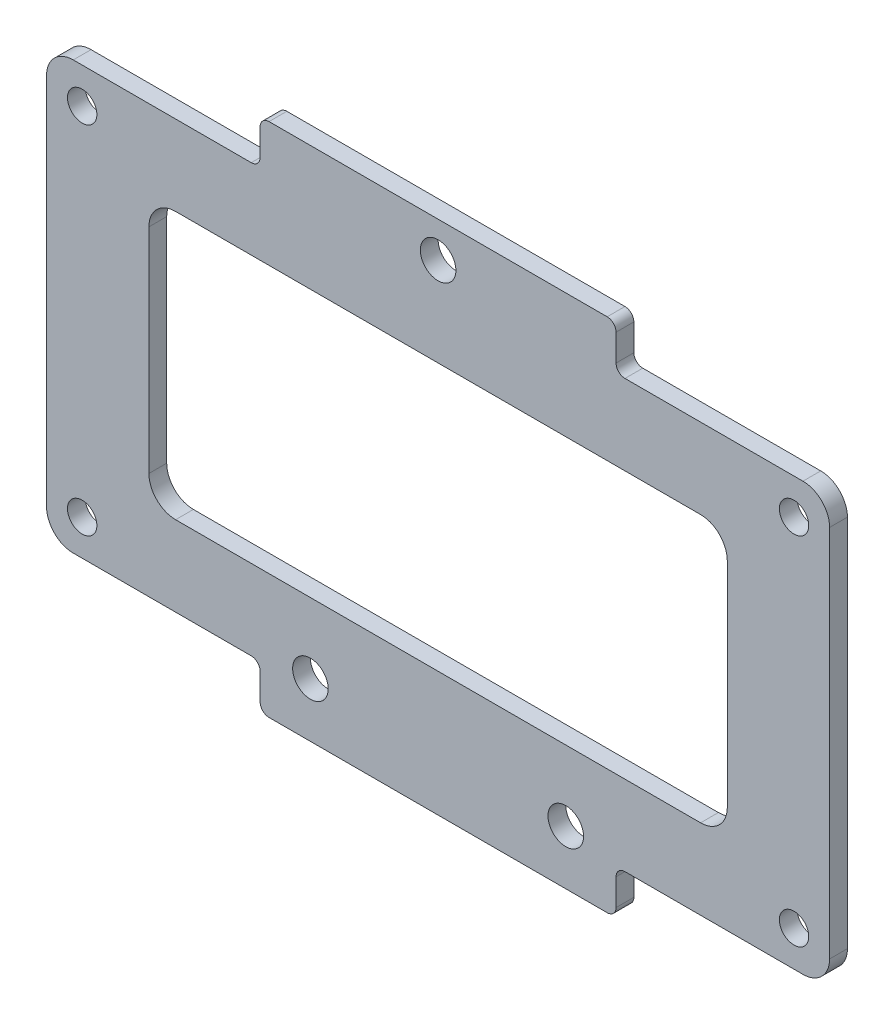
SolidWorks part; units mm, degrees
material "A-玻璃纤维"
ref_plane "前视基准面" through (0, 0, 0) normal (0, 0, 1) x (1, 0, 0)
ref_plane "上视基准面" through (0, 0, 0) normal (0, 1, 0) x (1, 0, 0)
ref_plane "右视基准面" through (0, 0, 0) normal (1, 0, 0) x (0, 0, -1)
sketch "草图1" plane through (0, 0, 0) normal (0, 0, 1) x (1, 0, 0)
  line L1 (40, -20) -> (-40, -20) construction
  line L2 (40, -20) -> (40, 20) construction
  line L3 (40, 20) -> (-40, 20) construction
  line L4 (-40, -20) -> (-40, 20) construction
  line L5 (40, -20) -> (-40, 20) construction
  line L6 (40, 20) -> (-40, -20) construction
  line L7 (44, -24) -> (-44, -24)
  line L8 (44, -24) -> (44, 24)
  line L9 (44, 24) -> (-44, 24)
  line L10 (-44, -24) -> (-44, 24)
  line L11 (44, -24) -> (-44, 24) construction
  line L12 (44, 24) -> (-44, -24) construction
  circle A0 centre (-40, 20) radius 1.65
  circle A1 centre (40, 20) radius 1.65
  circle A2 centre (40, -20) radius 1.65
  circle A3 centre (-40, -20) radius 1.65
  point P0 (0, 0)
  point P10 (0, 0)
  dimension "D3" = 3.3
  dimension "D4" = 3.3
  dimension "D5" = 3.3
  dimension "D6" = 3.3
  dimension "D1" = 40
  dimension "D2" = 80
  dimension "D7" = 48
  dimension "D8" = 88
extrude "凸台-拉伸1" add sketch "草图1" along normal blind 2
fillet "圆角1" radius 3 4 edges at (44, -24, 1) (44, 24, 1) (-44, -24, 1) (-44, 24, 1)
sketch "草图3" plane through (0, 0, 2) normal (0, 0, 1) x (1, 0, 0)
  line L0 (41, 24) -> (-41, 24) construction
  line L1 (20, 19) -> (-20, 19)
  line L2 (20, 19) -> (20, 29)
  line L3 (20, 29) -> (-20, 29)
  line L4 (-20, 19) -> (-20, 29)
  line L5 (20, 19) -> (-20, 29) construction
  line L6 (20, 29) -> (-20, 19) construction
  line L7 (-41, -24) -> (41, -24) construction
  line L8 (20, -29) -> (-20, -29)
  line L9 (20, -29) -> (20, -19)
  line L10 (20, -19) -> (-20, -19)
  line L11 (-20, -29) -> (-20, -19)
  line L12 (20, -29) -> (-20, -19) construction
  line L13 (20, -19) -> (-20, -29) construction
  point P0 (0, 24)
  point P7 (0, -24)
  dimension "D1" = 10
  dimension "D2" = 40
  dimension "D3" = 10
  dimension "D4" = 40
extrude "凸台-拉伸2" add sketch "草图3" against normal up to surface (2 mm away) up to face at (0, 0, 0)
sketch "草图2" plane through (0, 0, 2) normal (0, 0, 1) x (1, 0, 0)
  line L0 (-14.35, -22.8965) -> (14.35, -22.8965) construction
  line L1 (0, -22.8965) -> (0, 25) construction
  circle A0 centre (0, 25) radius 2
  circle A1 centre (-14.35, -22.8965) radius 2
  circle A2 centre (14.35, -22.8965) radius 2
  dimension "D1" = 4
  dimension "D2" = 4
  dimension "D3" = 4
  dimension "D4" = 28.7
  dimension "D5" = 50
  dimension "D6" = 50
  dimension "D7" = 25
extrude "切除-拉伸1" cut sketch "草图2" against normal blind 2
sketch "草图4" plane through (0, 0, 2) normal (0, 0, 1) x (1, 0, 0)
  line L1 (32.5, -15) -> (-32.5, -15)
  line L2 (32.5, -15) -> (32.5, 15)
  line L3 (32.5, 15) -> (-32.5, 15)
  line L4 (-32.5, -15) -> (-32.5, 15)
  line L5 (32.5, -15) -> (-32.5, 15) construction
  line L6 (32.5, 15) -> (-32.5, -15) construction
  point P0 (0, 0)
  dimension "D1" = 30
  dimension "D2" = 65
extrude "切除-拉伸2" cut sketch "草图4" against normal blind 2
fillet "圆角2" radius 3 4 edges at (-32.5, -15, 1) (32.5, -15, 1) (32.5, 15, 1) (-32.5, 15, 1)
fillet "圆角3" radius 1 8 edges at (20, -29, 1) (20, -24, 1) (-20, -29, 1) (-20, -24, 1) (-20, 24, 1) (-20, 29, 1) (20, 29, 1) (20, 24, 1)
